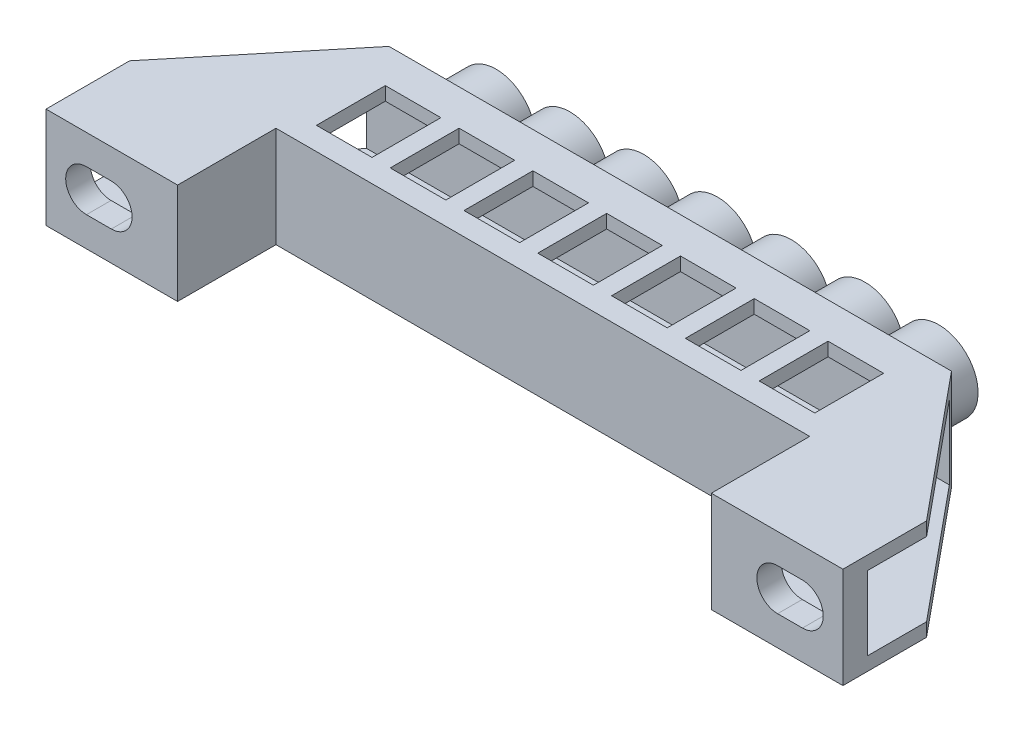
SolidWorks part; units mm, degrees
ref_plane "Front Plane" through (0, 0, 0) normal (0, 0, 1) x (1, 0, 0)
ref_plane "Top Plane" through (0, 0, 0) normal (0, 1, 0) x (1, 0, 0)
ref_plane "Right Plane" through (0, 0, 0) normal (1, 0, 0) x (0, 0, -1)
sketch "Sketch1" plane through (0, 0, 0) normal (0, 1, 0) x (1, 0, 0)
  line L0 (-41.148, -10.16) -> (-27.559, -10.16)
  line L1 (-27.559, -10.16) -> (-27.559, 0)
  line L2 (-27.559, 0) -> (27.559, 0)
  line L3 (27.559, 0) -> (27.559, -10.16)
  line L4 (27.559, -10.16) -> (41.148, -10.16)
  line L5 (41.148, -10.16) -> (41.148, -1.524)
  line L7 (-29.0449, 13.1572) -> (29.0449, 13.1572)
  line L9 (-41.148, -1.524) -> (-41.148, -10.16)
  line L10 (-41.148, -1.524) -> (-29.0449, 13.1572)
  line L11 (29.0449, 13.1572) -> (41.148, -1.524)
  line L12 (4.7498, 9.4615) -> (10.4902, 9.4615)
  line L13 (-2.8702, 9.4615) -> (2.8702, 9.4615)
  line L14 (-2.8702, 9.4615) -> (-2.8702, 2.3495)
  line L15 (-2.8702, 2.3495) -> (2.8702, 2.3495)
  line L16 (2.8702, 9.4615) -> (2.8702, 2.3495)
  line L17 (10.4902, 9.4615) -> (10.4902, 2.3495)
  line L18 (4.7498, 2.3495) -> (10.4902, 2.3495)
  line L19 (4.7498, 9.4615) -> (4.7498, 2.3495)
  line L20 (12.3698, 9.4615) -> (18.1102, 9.4615)
  line L21 (18.1102, 9.4615) -> (18.1102, 2.3495)
  line L22 (12.3698, 2.3495) -> (18.1102, 2.3495)
  line L23 (12.3698, 9.4615) -> (12.3698, 2.3495)
  line L24 (19.9898, 9.4615) -> (25.7302, 9.4615)
  line L25 (25.7302, 9.4615) -> (25.7302, 2.3495)
  line L26 (19.9898, 2.3495) -> (25.7302, 2.3495)
  line L27 (19.9898, 9.4615) -> (19.9898, 2.3495)
  line L28 (-10.4902, 9.4615) -> (-4.7498, 9.4615)
  line L29 (-4.7498, 9.4615) -> (-4.7498, 2.3495)
  line L30 (-10.4902, 2.3495) -> (-4.7498, 2.3495)
  line L31 (-10.4902, 9.4615) -> (-10.4902, 2.3495)
  line L32 (-18.1102, 9.4615) -> (-12.3698, 9.4615)
  line L33 (-12.3698, 9.4615) -> (-12.3698, 2.3495)
  line L34 (-18.1102, 2.3495) -> (-12.3698, 2.3495)
  line L35 (-18.1102, 9.4615) -> (-18.1102, 2.3495)
  line L36 (-25.7302, 9.4615) -> (-19.9898, 9.4615)
  line L37 (-19.9898, 9.4615) -> (-19.9898, 2.3495)
  line L38 (-25.7302, 2.3495) -> (-19.9898, 2.3495)
  line L39 (-25.7302, 9.4615) -> (-25.7302, 2.3495)
  point P7 (0, 0)
  point P12 (0, 13.1572)
  point P17 (0, 2.3495)
  dimension "D1" = 13.589
  dimension "D2" = 10.16
  dimension "D3" = 55.118
  dimension "D4" = 58.0898
  dimension "D5" = 8.636
  dimension "D6" = 13.1572
  dimension "D7" = 5.7404
  dimension "D8" = 7.112
  dimension "D9" = 2.3495
  dimension "D10" = 4
  dimension "D11" = 4
extrude "Boss-Extrude1" add sketch "Sketch1" along normal blind 10.414
sketch "Sketch3" plane through (0, 0, 10.16) normal (0, 0, 1) x (1, 0, 0)
  line L0 (41.148, 10.414) -> (41.148, 0) construction
  line L1 (41.148, 1.397) -> (29.0068, 1.397)
  line L2 (41.148, 1.397) -> (41.148, 9.017)
  line L3 (41.148, 9.017) -> (29.0068, 9.017)
  line L4 (29.0068, 1.397) -> (29.0068, 9.017)
  point P6 (41.148, 5.207)
  point P7 (41.148, 5.207)
  dimension "D1" = 7.62
  dimension "D2" = 12.1412
extrude "Cut-Extrude1" cut sketch "Sketch3" against normal offset from surface (19.5072 mm away) 1.27 from offset 2.54 up to face at (0, 5.207, -13.1572) offset against normal yes
sketch "Sketch4" plane through (29.0068, 0, 0) normal (1, 0, 0) x (0, 0, -1)
  line L0 (11.8872, 1.397) -> (-7.62, 1.397) construction
  line L1 (11.8872, 9.017) -> (0.9652, 9.017)
  line L2 (11.8872, 9.017) -> (11.8872, 1.397)
  line L3 (11.8872, 1.397) -> (0.9652, 1.397)
  line L4 (0.9652, 9.017) -> (0.9652, 1.397)
  dimension "D1" = 10.922
extrude "Cut-Extrude2" cut sketch "Sketch4" against normal through all
sketch "Sketch5" plane through (0, 0, 7.62) normal (0, 0, -1) x (-1, 0, 0)
  line L0 (-34.4043, 5.207) -> (-36.9697, 5.207) construction
  line L1 (-34.4043, 3.0607) -> (-36.9697, 3.0607)
  line L2 (-34.4043, 7.3533) -> (-36.9697, 7.3533)
  line L3 (-41.148, 1.397) -> (-41.148, 9.017) construction
  arc A0 (-34.4043, 3.0607) -> (-34.4043, 7.3533) centre (-34.4043, 5.207) ccw
  arc A1 (-36.9697, 7.3533) -> (-36.9697, 3.0607) centre (-36.9697, 5.207) ccw
  point P2 (-35.687, 5.207)
  point P7 (-39.116, 5.207)
  point P10 (-32.258, 5.207)
  point P11 (-41.148, 5.207)
  point P12 (-29.5121, 11.662)
  dimension "D1" = 2.032
  dimension "D2" = 6.858
  dimension "D3" = 4.2926
extrude "Cut-Extrude3" cut sketch "Sketch5" against normal through all
ref_point "Point1"
ref_plane "Plane1" through (0, 0, 0) normal (1, 0, 0) x (0, 0, -1)
mirror "Mirror1" about plane through (0, 0, 0) normal (1, 0, 0) of "Cut-Extrude1", "Cut-Extrude3"
sketch "Sketch6" plane through (0, 0, -13.1572) normal (0, 0, -1) x (-1, 0, 0)
  arc A0 (-3.81, 3.6022) -> (3.81, 3.6022) centre (0, 4.9795) ccw
  circle A1 centre (0, 4.9795) radius 3.175
  arc A2 (3.81, 3.6022) -> (11.43, 3.6022) centre (7.62, 4.9795) ccw
  circle A3 centre (7.62, 4.9795) radius 3.175
  arc A4 (11.43, 3.6022) -> (19.05, 3.6022) centre (15.24, 4.9795) ccw
  circle A5 centre (15.24, 4.9795) radius 3.175
  arc A6 (19.05, 3.6022) -> (19.05, 6.3568) centre (22.86, 4.9795) ccw
  circle A7 centre (22.86, 4.9795) radius 3.175
  circle A8 centre (-7.62, 4.9795) radius 3.175
  arc A9 (-11.43, 3.6022) -> (-3.81, 3.6022) centre (-7.62, 4.9795) ccw
  circle A10 centre (-15.24, 4.9795) radius 3.175
  arc A11 (-19.05, 3.6022) -> (-11.43, 3.6022) centre (-15.24, 4.9795) ccw
  circle A12 centre (-22.86, 4.9795) radius 3.175
  arc A13 (-19.05, 6.3568) -> (-19.05, 3.6022) centre (-22.86, 4.9795) ccw
  arc A14 (-11.43, 6.3568) -> (-19.05, 6.3568) centre (-15.24, 4.9795) ccw
  arc A15 (-3.81, 6.3568) -> (-11.43, 6.3568) centre (-7.62, 4.9795) ccw
  arc A16 (3.81, 6.3568) -> (-3.81, 6.3568) centre (0, 4.9795) ccw
  arc A17 (11.43, 6.3568) -> (3.81, 6.3568) centre (7.62, 4.9795) ccw
  arc A18 (19.05, 6.3568) -> (11.43, 6.3568) centre (15.24, 4.9795) ccw
  dimension "D1" = 8.1026
  dimension "D2" = 6.35
  dimension "D3" = 4
extrude "Boss-Extrude2" add sketch "Sketch6" along normal blind 4.8768
